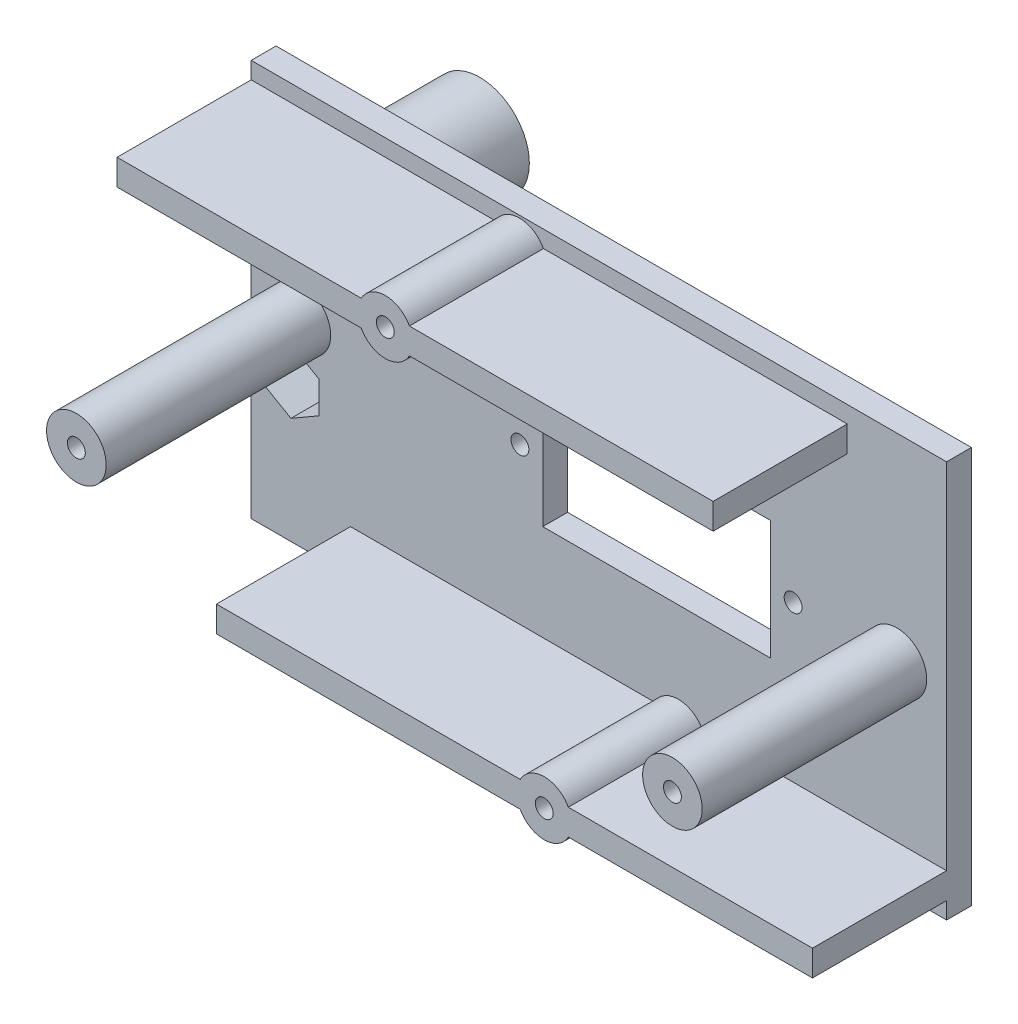
SolidWorks part; units mm, degrees
ref_plane "Front Plane" through (0, 0, 0) normal (0, 0, 1) x (1, 0, 0)
ref_plane "Top Plane" through (0, 0, 0) normal (0, 1, 0) x (1, 0, 0)
ref_plane "Right Plane" through (0, 0, 0) normal (1, 0, 0) x (0, 0, -1)
sketch "Sketch1" plane through (0, 0, 0) normal (0, 0, 1) x (1, 0, 0)
  line L0 (-35, -19.975) -> (35, -19.975)
  line L1 (35, -19.975) -> (35, 19.975)
  line L2 (35, 19.975) -> (-35, 19.975)
  line L3 (-35, 19.975) -> (-35, -19.975)
extrude "Boss-Extrude1" add sketch "Sketch1" along normal blind 2.5 from offset 2.5
sketch "Sketch2" plane through (0, 0, 0) normal (0, 0, 1) x (1, 0, 0)
  line L0 (-35, 15.675) -> (25, 15.675)
  line L1 (25, 15.675) -> (25, 18.275)
  line L2 (25, 18.275) -> (-35, 18.275)
  line L3 (-35, 18.275) -> (-35, 15.675)
extrude "Boss-Extrude2" add sketch "Sketch2" along normal blind 13.5
sketch "Sketch3" plane through (0, 0, 0) normal (0, 0, 1) x (1, 0, 0)
  line L0 (-25, -18.275) -> (35, -18.275)
  line L1 (35, -18.275) -> (35, -15.675)
  line L2 (35, -15.675) -> (-25, -15.675)
  line L3 (-25, -15.675) -> (-25, -18.275)
extrude "Boss-Extrude3" add sketch "Sketch3" along normal blind 13.5
sketch "Sketch4" plane through (0, 0, 0) normal (0, 0, 1) x (1, 0, 0)
  circle A0 centre (-8, 16.975) radius 2.75
  circle A1 centre (8, -16.975) radius 2.75
extrude "Boss-Extrude4" add sketch "Sketch4" along normal blind 13.5
sketch "Sketch5" plane through (0, 0, 0) normal (0, 0, 1) x (1, 0, 0)
  circle A0 centre (-31, 6) radius 5
  circle A1 centre (-31, -6) radius 5
extrude "Boss-Extrude5" add sketch "Sketch5" along normal blind 16.5 from offset 19
sketch "Sketch6" plane through (0, 0, 0) normal (0, 0, 1) x (1, 0, 0)
  circle A0 centre (30, 0) radius 3
  circle A1 centre (-30, 0) radius 3
extrude "Boss-Extrude6" add sketch "Sketch6" along normal blind 22.6
sketch "Sketch7" plane through (0, 0, 0) normal (0, 0, 1) x (1, 0, 0)
  circle A0 centre (30, 0) radius 0.9
  circle A1 centre (-30, 0) radius 0.9
extrude "Cut-Extrude1" cut sketch "Sketch7" along normal blind 8.1 from offset 14.6
sketch "Sketch8" plane through (0, 0, 0) normal (0, 0, 1) x (1, 0, 0)
  line L0 (-5.65, -6) -> (17.25, -6)
  line L1 (17.25, -6) -> (17.25, 6)
  line L2 (17.25, 6) -> (-5.65, 6)
  line L3 (-5.65, 6) -> (-5.65, -6)
extrude "Cut-Extrude2" cut sketch "Sketch8" against normal through all and the other way through all
sketch "Sketch9" plane through (0, 0, 0) normal (0, 0, 1) x (1, 0, 0)
  circle A0 centre (-7.95, 0) radius 0.9
  circle A1 centre (19.55, 0) radius 0.9
extrude "Cut-Extrude3" cut sketch "Sketch9" against normal through all and the other way through all
sketch "Sketch10" plane through (0, 0, 0) normal (0, 0, 1) x (1, 0, 0)
  circle A0 centre (-8, 16.975) radius 0.9
  circle A1 centre (8, -16.975) radius 0.9
extrude "Cut-Extrude4" cut sketch "Sketch10" against normal through all and the other way through all
sketch "Sketch11" plane through (0, 0, 0) normal (0, 0, 1) x (1, 0, 0)
  circle A0 centre (-31, 6) radius 1.725
  circle A1 centre (-31, -6) radius 1.725
extrude "Cut-Extrude5" cut sketch "Sketch11" against normal through all and the other way through all
sketch "Sketch12" plane through (0, 0, 0) normal (0, 0, 1) x (1, 0, 0)
  line L0 (-28.2, 7.6166) -> (-31, 9.2332)
  line L1 (-31, 9.2332) -> (-33.8, 7.6166)
  line L2 (-33.8, 7.6166) -> (-33.8, 4.3834)
  line L3 (-33.8, 4.3834) -> (-31, 2.7668)
  line L4 (-31, 2.7668) -> (-28.2, 4.3834)
  line L5 (-28.2, 4.3834) -> (-28.2, 7.6166)
  line L6 (-28.2, -4.3834) -> (-31, -2.7668)
  line L7 (-31, -2.7668) -> (-33.8, -4.3834)
  line L8 (-33.8, -4.3834) -> (-33.8, -7.6166)
  line L9 (-33.8, -7.6166) -> (-31, -9.2332)
  line L10 (-31, -9.2332) -> (-28.2, -7.6166)
  line L11 (-28.2, -7.6166) -> (-28.2, -4.3834)
extrude "Cut-Extrude6" cut sketch "Sketch12" along normal blind 4.2 from offset 4.2
